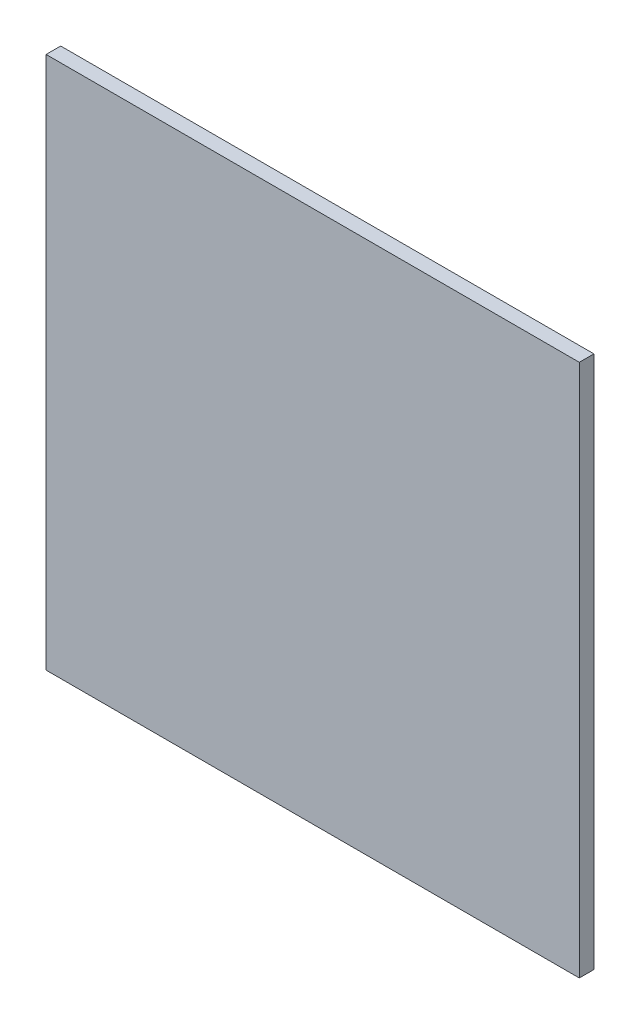
SolidWorks part; units mm, degrees
ref_plane "Front Plane" through (0, 0, 0) normal (0, 0, 1) x (1, 0, 0)
ref_plane "Top Plane" through (0, 0, 0) normal (0, 1, 0) x (1, 0, 0)
ref_plane "Right Plane" through (0, 0, 0) normal (1, 0, 0) x (0, 0, -1)
sketch "Sketch1" plane through (0, 0, 0) normal (0, 0, 1) x (1, 0, 0)
  line L1 (-36.5, 36.5) -> (36.5, 36.5)
  line L2 (-36.5, 36.5) -> (-36.5, -36.5)
  line L3 (-36.5, -36.5) -> (36.5, -36.5)
  line L4 (36.5, 36.5) -> (36.5, -36.5)
  line L5 (-36.5, 36.5) -> (36.5, -36.5) construction
  line L6 (-36.5, -36.5) -> (36.5, 36.5) construction
  point P0 (0, 0)
  dimension "D1" = 73
extrude "Boss-Extrude1" add sketch "Sketch1" along normal blind 2
